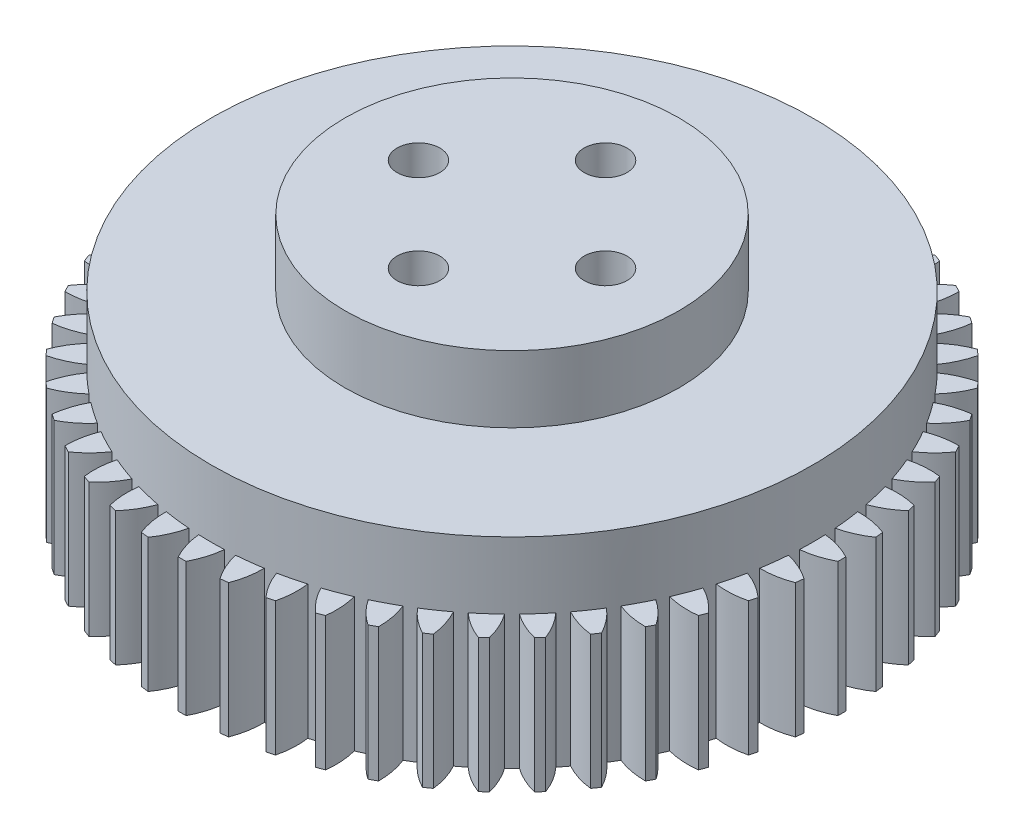
SolidWorks part; units mm, degrees
ref_plane "Front" through (0, 0, 0) normal (0, 0, 1) x (1, 0, 0)
ref_plane "Top" through (0, 0, 0) normal (0, 1, 0) x (1, 0, 0)
ref_plane "Right" through (0, 0, 0) normal (1, 0, 0) x (0, 0, -1)
sketch "Sketch1" plane through (0, 0, 0) normal (0, 1, 0) x (1, 0, 0)
  circle A0 centre (0, 0) radius 22.5
  dimension "D1" = 45
extrude "Boss-Extrude1" add sketch "Sketch1" along normal blind 15
sketch "Sketch2" plane through (0, 15, 0) normal (0, 1, 0) x (1, 0, 0)
  circle A0 centre (0, 0) radius 12.5
  dimension "D1" = 25
extrude "Boss-Extrude2" add sketch "Sketch2" along normal blind 5
sketch "Sketch3" plane through (0, 20, 0) normal (0, 1, 0) x (1, 0, 0)
  circle A1 centre (7, 0) radius 1.6
  circle A2 centre (0, -7) radius 1.6
  circle A3 centre (-7, 0) radius 1.6
  circle A4 centre (0, 7) radius 1.6
  point P13 (0, 0)
  dimension "D2" = 3.2
  dimension "D4" = 4
extrude "Cut-Extrude2" cut sketch "Sketch3" against normal blind 21
sketch "Sketch4" plane through (0, 0, 0) normal (0, -1, 0) x (1, 0, 0)
  circle A0 centre (0, -7) radius 3
  circle A1 centre (-7, 0) radius 3
  circle A2 centre (0, 7) radius 3
  circle A3 centre (7, 0) radius 3
  point P11 (0, 0)
  dimension "D1" = 6
  dimension "D2" = 4
extrude "Cut-Extrude3" cut sketch "Sketch4" against normal blind 4
sketch "Sketch5" plane through (0, 0, 0) normal (0, -1, 0) x (1, 0, 0)
  arc A0 (-0.2927, 24.6828) -> (-0.9725, 22.4) centre (5.0034, 21.8629) ccw
  arc A1 (0.9725, 22.4) -> (0.2927, 24.6828) centre (-5.0034, 21.8629) ccw
  arc A2 (0.2927, 24.6828) -> (-0.2927, 24.6828) centre (0, 0) ccw
  arc A3 (-0.9725, 22.4) -> (0.9725, 22.4) centre (0, 0) cw
  arc A4 (2.6847, 24.5381) -> (1.7346, 22.3539) centre (7.6022, 21.1004) ccw
  arc A5 (3.6654, 22.1195) -> (3.2657, 24.4675) centre (-2.3317, 22.3066) ccw
  arc A6 (3.2657, 24.4675) -> (2.6847, 24.5381) centre (0, 0) ccw
  arc A7 (1.7346, 22.3539) -> (3.6654, 22.1195) centre (0, 0) cw
  arc A8 (5.6228, 24.0356) -> (4.4164, 21.9818) centre (10.0902, 20.0302) ccw
  arc A9 (6.3049, 21.5164) -> (6.1911, 23.8955) centre (0.3741, 22.425) ccw
  arc A10 (6.1911, 23.8955) -> (5.6228, 24.0356) centre (0, 0) ccw
  arc A11 (4.4164, 21.9818) -> (6.3049, 21.5164) centre (0, 0) cw
  arc A12 (8.479, 23.1826) -> (7.0339, 21.2892) centre (12.431, 18.6679) ccw
  arc A13 (8.8524, 20.5995) -> (9.0263, 22.975) centre (3.0744, 22.2164) ccw
  arc A14 (9.0263, 22.975) -> (8.479, 23.1826) centre (0, 0) ccw
  arc A15 (7.0339, 21.2892) -> (8.8524, 20.5995) centre (0, 0) cw
  arc A16 (11.2115, 21.9915) -> (9.5487, 20.2862) centre (14.5905, 17.0334) ccw
  arc A17 (11.2709, 19.3823) -> (11.7298, 21.7195) centre (5.7299, 21.6838) ccw
  arc A18 (11.7298, 21.7195) -> (11.2115, 21.9915) centre (0, 0) ccw
  arc A19 (9.5487, 20.2862) -> (11.2709, 19.3823) centre (0, 0) cw
  arc A20 (13.7806, 20.4798) -> (11.9243, 18.9873) centre (16.5373, 15.1506) ccw
  arc A21 (13.525, 17.8824) -> (14.2623, 20.1473) centre (8.3018, 20.8351) ccw
  arc A22 (14.2623, 20.1473) -> (13.7806, 20.4798) centre (0, 0) ccw
  arc A23 (11.9243, 18.9873) -> (13.525, 17.8824) centre (0, 0) cw
  arc A24 (16.1486, 18.6694) -> (14.126, 17.4115) centre (18.2429, 13.0467) ccw
  arc A25 (15.5819, 16.1218) -> (16.5868, 18.2812) centre (10.7527, 19.6825) ccw
  arc A26 (16.5868, 18.2812) -> (16.1486, 18.6694) centre (0, 0) ccw
  arc A27 (14.126, 17.4115) -> (15.5819, 16.1218) centre (0, 0) cw
  arc A28 (18.2812, 16.5868) -> (16.1218, 15.5819) centre (19.6825, 10.7527) ccw
  arc A29 (17.4115, 14.126) -> (18.6694, 16.1486) centre (13.0467, 18.2429) ccw
  arc A30 (18.6694, 16.1486) -> (18.2812, 16.5868) centre (0, 0) ccw
  arc A31 (16.1218, 15.5819) -> (17.4115, 14.126) centre (0, 0) cw
  arc A32 (20.1473, 14.2623) -> (17.8824, 13.525) centre (20.8351, 8.3018) ccw
  arc A33 (18.9873, 11.9243) -> (20.4798, 13.7806) centre (15.1506, 16.5373) ccw
  arc A34 (20.4798, 13.7806) -> (20.1473, 14.2623) centre (0, 0) ccw
  arc A35 (17.8824, 13.525) -> (18.9873, 11.9243) centre (0, 0) cw
  arc A36 (21.7195, 11.7298) -> (19.3823, 11.2709) centre (21.6838, 5.7299) ccw
  arc A37 (20.2862, 9.5487) -> (21.9915, 11.2115) centre (17.0334, 14.5905) ccw
  arc A38 (21.9915, 11.2115) -> (21.7195, 11.7298) centre (0, 0) ccw
  arc A39 (19.3823, 11.2709) -> (20.2862, 9.5487) centre (0, 0) cw
  arc A40 (22.975, 9.0263) -> (20.5995, 8.8524) centre (22.2164, 3.0744) ccw
  arc A41 (21.2892, 7.0339) -> (23.1826, 8.479) centre (18.6679, 12.431) ccw
  arc A42 (23.1826, 8.479) -> (22.975, 9.0263) centre (0, 0) ccw
  arc A43 (20.5995, 8.8524) -> (21.2892, 7.0339) centre (0, 0) cw
  arc A44 (23.8955, 6.1911) -> (21.5164, 6.3049) centre (22.425, 0.3741) ccw
  arc A45 (21.9818, 4.4164) -> (24.0356, 5.6228) centre (20.0302, 10.0902) ccw
  arc A46 (24.0356, 5.6228) -> (23.8955, 6.1911) centre (0, 0) ccw
  arc A47 (21.5164, 6.3049) -> (21.9818, 4.4164) centre (0, 0) cw
  arc A48 (24.4675, 3.2657) -> (22.1195, 3.6654) centre (22.3066, -2.3317) ccw
  arc A49 (22.3539, 1.7346) -> (24.5381, 2.6847) centre (21.1004, 7.6022) ccw
  arc A50 (24.5381, 2.6847) -> (24.4675, 3.2657) centre (0, 0) ccw
  arc A51 (22.1195, 3.6654) -> (22.3539, 1.7346) centre (0, 0) cw
  arc A52 (24.6828, 0.2927) -> (22.4, 0.9725) centre (21.8629, -5.0034) ccw
  arc A53 (22.4, -0.9725) -> (24.6828, -0.2927) centre (21.8629, 5.0034) ccw
  arc A54 (24.6828, -0.2927) -> (24.6828, 0.2927) centre (0, 0) ccw
  arc A55 (22.4, 0.9725) -> (22.4, -0.9725) centre (0, 0) cw
  arc A56 (24.5381, -2.6847) -> (22.3539, -1.7346) centre (21.1004, -7.6022) ccw
  arc A57 (22.1195, -3.6654) -> (24.4675, -3.2657) centre (22.3066, 2.3317) ccw
  arc A58 (24.4675, -3.2657) -> (24.5381, -2.6847) centre (0, 0) ccw
  arc A59 (22.3539, -1.7346) -> (22.1195, -3.6654) centre (0, 0) cw
  arc A60 (24.0356, -5.6228) -> (21.9818, -4.4164) centre (20.0302, -10.0902) ccw
  arc A61 (21.5164, -6.3049) -> (23.8955, -6.1911) centre (22.425, -0.3741) ccw
  arc A62 (23.8955, -6.1911) -> (24.0356, -5.6228) centre (0, 0) ccw
  arc A63 (21.9818, -4.4164) -> (21.5164, -6.3049) centre (0, 0) cw
  arc A64 (23.1826, -8.479) -> (21.2892, -7.0339) centre (18.6679, -12.431) ccw
  arc A65 (20.5995, -8.8524) -> (22.975, -9.0263) centre (22.2164, -3.0744) ccw
  arc A66 (22.975, -9.0263) -> (23.1826, -8.479) centre (0, 0) ccw
  arc A67 (21.2892, -7.0339) -> (20.5995, -8.8524) centre (0, 0) cw
  arc A68 (21.9915, -11.2115) -> (20.2862, -9.5487) centre (17.0334, -14.5905) ccw
  arc A69 (19.3823, -11.2709) -> (21.7195, -11.7298) centre (21.6838, -5.7299) ccw
  arc A70 (21.7195, -11.7298) -> (21.9915, -11.2115) centre (0, 0) ccw
  arc A71 (20.2862, -9.5487) -> (19.3823, -11.2709) centre (0, 0) cw
  arc A72 (20.4798, -13.7806) -> (18.9873, -11.9243) centre (15.1506, -16.5373) ccw
  arc A73 (17.8824, -13.525) -> (20.1473, -14.2623) centre (20.8351, -8.3018) ccw
  arc A74 (20.1473, -14.2623) -> (20.4798, -13.7806) centre (0, 0) ccw
  arc A75 (18.9873, -11.9243) -> (17.8824, -13.525) centre (0, 0) cw
  arc A76 (18.6694, -16.1486) -> (17.4115, -14.126) centre (13.0467, -18.2429) ccw
  arc A77 (16.1218, -15.5819) -> (18.2812, -16.5868) centre (19.6825, -10.7527) ccw
  arc A78 (18.2812, -16.5868) -> (18.6694, -16.1486) centre (0, 0) ccw
  arc A79 (17.4115, -14.126) -> (16.1218, -15.5819) centre (0, 0) cw
  arc A80 (16.5868, -18.2812) -> (15.5819, -16.1218) centre (10.7527, -19.6825) ccw
  arc A81 (14.126, -17.4115) -> (16.1486, -18.6694) centre (18.2429, -13.0467) ccw
  arc A82 (16.1486, -18.6694) -> (16.5868, -18.2812) centre (0, 0) ccw
  arc A83 (15.5819, -16.1218) -> (14.126, -17.4115) centre (0, 0) cw
  arc A84 (14.2623, -20.1473) -> (13.525, -17.8824) centre (8.3018, -20.8351) ccw
  arc A85 (11.9243, -18.9873) -> (13.7806, -20.4798) centre (16.5373, -15.1506) ccw
  arc A86 (13.7806, -20.4798) -> (14.2623, -20.1473) centre (0, 0) ccw
  arc A87 (13.525, -17.8824) -> (11.9243, -18.9873) centre (0, 0) cw
  arc A88 (11.7298, -21.7195) -> (11.2709, -19.3823) centre (5.7299, -21.6838) ccw
  arc A89 (9.5487, -20.2862) -> (11.2115, -21.9915) centre (14.5905, -17.0334) ccw
  arc A90 (11.2115, -21.9915) -> (11.7298, -21.7195) centre (0, 0) ccw
  arc A91 (11.2709, -19.3823) -> (9.5487, -20.2862) centre (0, 0) cw
  arc A92 (9.0263, -22.975) -> (8.8524, -20.5995) centre (3.0744, -22.2164) ccw
  arc A93 (7.0339, -21.2892) -> (8.479, -23.1826) centre (12.431, -18.6679) ccw
  arc A94 (8.479, -23.1826) -> (9.0263, -22.975) centre (0, 0) ccw
  arc A95 (8.8524, -20.5995) -> (7.0339, -21.2892) centre (0, 0) cw
  arc A96 (6.1911, -23.8955) -> (6.3049, -21.5164) centre (0.3741, -22.425) ccw
  arc A97 (4.4164, -21.9818) -> (5.6228, -24.0356) centre (10.0902, -20.0302) ccw
  arc A98 (5.6228, -24.0356) -> (6.1911, -23.8955) centre (0, 0) ccw
  arc A99 (6.3049, -21.5164) -> (4.4164, -21.9818) centre (0, 0) cw
  arc A100 (3.2657, -24.4675) -> (3.6654, -22.1195) centre (-2.3317, -22.3066) ccw
  arc A101 (1.7346, -22.3539) -> (2.6847, -24.5381) centre (7.6022, -21.1004) ccw
  arc A102 (2.6847, -24.5381) -> (3.2657, -24.4675) centre (0, 0) ccw
  arc A103 (3.6654, -22.1195) -> (1.7346, -22.3539) centre (0, 0) cw
  arc A104 (0.2927, -24.6828) -> (0.9725, -22.4) centre (-5.0034, -21.8629) ccw
  arc A105 (-0.9725, -22.4) -> (-0.2927, -24.6828) centre (5.0034, -21.8629) ccw
  arc A106 (-0.2927, -24.6828) -> (0.2927, -24.6828) centre (0, 0) ccw
  arc A107 (0.9725, -22.4) -> (-0.9725, -22.4) centre (0, 0) cw
  arc A108 (-2.6847, -24.5381) -> (-1.7346, -22.3539) centre (-7.6022, -21.1004) ccw
  arc A109 (-3.6654, -22.1195) -> (-3.2657, -24.4675) centre (2.3317, -22.3066) ccw
  arc A110 (-3.2657, -24.4675) -> (-2.6847, -24.5381) centre (0, 0) ccw
  arc A111 (-1.7346, -22.3539) -> (-3.6654, -22.1195) centre (0, 0) cw
  arc A112 (-5.6228, -24.0356) -> (-4.4164, -21.9818) centre (-10.0902, -20.0302) ccw
  arc A113 (-6.3049, -21.5164) -> (-6.1911, -23.8955) centre (-0.3741, -22.425) ccw
  arc A114 (-6.1911, -23.8955) -> (-5.6228, -24.0356) centre (0, 0) ccw
  arc A115 (-4.4164, -21.9818) -> (-6.3049, -21.5164) centre (0, 0) cw
  arc A116 (-8.479, -23.1826) -> (-7.0339, -21.2892) centre (-12.431, -18.6679) ccw
  arc A117 (-8.8524, -20.5995) -> (-9.0263, -22.975) centre (-3.0744, -22.2164) ccw
  arc A118 (-9.0263, -22.975) -> (-8.479, -23.1826) centre (0, 0) ccw
  arc A119 (-7.0339, -21.2892) -> (-8.8524, -20.5995) centre (0, 0) cw
  arc A120 (-11.2115, -21.9915) -> (-9.5487, -20.2862) centre (-14.5905, -17.0334) ccw
  arc A121 (-11.2709, -19.3823) -> (-11.7298, -21.7195) centre (-5.7299, -21.6838) ccw
  arc A122 (-11.7298, -21.7195) -> (-11.2115, -21.9915) centre (0, 0) ccw
  arc A123 (-9.5487, -20.2862) -> (-11.2709, -19.3823) centre (0, 0) cw
  arc A124 (-13.7806, -20.4798) -> (-11.9243, -18.9873) centre (-16.5373, -15.1506) ccw
  arc A125 (-13.525, -17.8824) -> (-14.2623, -20.1473) centre (-8.3018, -20.8351) ccw
  arc A126 (-14.2623, -20.1473) -> (-13.7806, -20.4798) centre (0, 0) ccw
  arc A127 (-11.9243, -18.9873) -> (-13.525, -17.8824) centre (0, 0) cw
  arc A128 (-16.1486, -18.6694) -> (-14.126, -17.4115) centre (-18.2429, -13.0467) ccw
  arc A129 (-15.5819, -16.1218) -> (-16.5868, -18.2812) centre (-10.7527, -19.6825) ccw
  arc A130 (-16.5868, -18.2812) -> (-16.1486, -18.6694) centre (0, 0) ccw
  arc A131 (-14.126, -17.4115) -> (-15.5819, -16.1218) centre (0, 0) cw
  arc A132 (-18.2812, -16.5868) -> (-16.1218, -15.5819) centre (-19.6825, -10.7527) ccw
  arc A133 (-17.4115, -14.126) -> (-18.6694, -16.1486) centre (-13.0467, -18.2429) ccw
  arc A134 (-18.6694, -16.1486) -> (-18.2812, -16.5868) centre (0, 0) ccw
  arc A135 (-16.1218, -15.5819) -> (-17.4115, -14.126) centre (0, 0) cw
  arc A136 (-20.1473, -14.2623) -> (-17.8824, -13.525) centre (-20.8351, -8.3018) ccw
  arc A137 (-18.9873, -11.9243) -> (-20.4798, -13.7806) centre (-15.1506, -16.5373) ccw
  arc A138 (-20.4798, -13.7806) -> (-20.1473, -14.2623) centre (0, 0) ccw
  arc A139 (-17.8824, -13.525) -> (-18.9873, -11.9243) centre (0, 0) cw
  arc A140 (-21.7195, -11.7298) -> (-19.3823, -11.2709) centre (-21.6838, -5.7299) ccw
  arc A141 (-20.2862, -9.5487) -> (-21.9915, -11.2115) centre (-17.0334, -14.5905) ccw
  arc A142 (-21.9915, -11.2115) -> (-21.7195, -11.7298) centre (0, 0) ccw
  arc A143 (-19.3823, -11.2709) -> (-20.2862, -9.5487) centre (0, 0) cw
  arc A144 (-22.975, -9.0263) -> (-20.5995, -8.8524) centre (-22.2164, -3.0744) ccw
  arc A145 (-21.2892, -7.0339) -> (-23.1826, -8.479) centre (-18.6679, -12.431) ccw
  arc A146 (-23.1826, -8.479) -> (-22.975, -9.0263) centre (0, 0) ccw
  arc A147 (-20.5995, -8.8524) -> (-21.2892, -7.0339) centre (0, 0) cw
  arc A148 (-23.8955, -6.1911) -> (-21.5164, -6.3049) centre (-22.425, -0.3741) ccw
  arc A149 (-21.9818, -4.4164) -> (-24.0356, -5.6228) centre (-20.0302, -10.0902) ccw
  arc A150 (-24.0356, -5.6228) -> (-23.8955, -6.1911) centre (0, 0) ccw
  arc A151 (-21.5164, -6.3049) -> (-21.9818, -4.4164) centre (0, 0) cw
  arc A152 (-24.4675, -3.2657) -> (-22.1195, -3.6654) centre (-22.3066, 2.3317) ccw
  arc A153 (-22.3539, -1.7346) -> (-24.5381, -2.6847) centre (-21.1004, -7.6022) ccw
  arc A154 (-24.5381, -2.6847) -> (-24.4675, -3.2657) centre (0, 0) ccw
  arc A155 (-22.1195, -3.6654) -> (-22.3539, -1.7346) centre (0, 0) cw
  arc A156 (-24.6828, -0.2927) -> (-22.4, -0.9725) centre (-21.8629, 5.0034) ccw
  arc A157 (-22.4, 0.9725) -> (-24.6828, 0.2927) centre (-21.8629, -5.0034) ccw
  arc A158 (-24.6828, 0.2927) -> (-24.6828, -0.2927) centre (0, 0) ccw
  arc A159 (-22.4, -0.9725) -> (-22.4, 0.9725) centre (0, 0) cw
  arc A160 (-24.5381, 2.6847) -> (-22.3539, 1.7346) centre (-21.1004, 7.6022) ccw
  arc A161 (-22.1195, 3.6654) -> (-24.4675, 3.2657) centre (-22.3066, -2.3317) ccw
  arc A162 (-24.4675, 3.2657) -> (-24.5381, 2.6847) centre (0, 0) ccw
  arc A163 (-22.3539, 1.7346) -> (-22.1195, 3.6654) centre (0, 0) cw
  arc A164 (-24.0356, 5.6228) -> (-21.9818, 4.4164) centre (-20.0302, 10.0902) ccw
  arc A165 (-21.5164, 6.3049) -> (-23.8955, 6.1911) centre (-22.425, 0.3741) ccw
  arc A166 (-23.8955, 6.1911) -> (-24.0356, 5.6228) centre (0, 0) ccw
  arc A167 (-21.9818, 4.4164) -> (-21.5164, 6.3049) centre (0, 0) cw
  arc A168 (-23.1826, 8.479) -> (-21.2892, 7.0339) centre (-18.6679, 12.431) ccw
  arc A169 (-20.5995, 8.8524) -> (-22.975, 9.0263) centre (-22.2164, 3.0744) ccw
  arc A170 (-22.975, 9.0263) -> (-23.1826, 8.479) centre (0, 0) ccw
  arc A171 (-21.2892, 7.0339) -> (-20.5995, 8.8524) centre (0, 0) cw
  arc A172 (-21.9915, 11.2115) -> (-20.2862, 9.5487) centre (-17.0334, 14.5905) ccw
  arc A173 (-19.3823, 11.2709) -> (-21.7195, 11.7298) centre (-21.6838, 5.7299) ccw
  arc A174 (-21.7195, 11.7298) -> (-21.9915, 11.2115) centre (0, 0) ccw
  arc A175 (-20.2862, 9.5487) -> (-19.3823, 11.2709) centre (0, 0) cw
  arc A176 (-20.4798, 13.7806) -> (-18.9873, 11.9243) centre (-15.1506, 16.5373) ccw
  arc A177 (-17.8824, 13.525) -> (-20.1473, 14.2623) centre (-20.8351, 8.3018) ccw
  arc A178 (-20.1473, 14.2623) -> (-20.4798, 13.7806) centre (0, 0) ccw
  arc A179 (-18.9873, 11.9243) -> (-17.8824, 13.525) centre (0, 0) cw
  arc A180 (-18.6694, 16.1486) -> (-17.4115, 14.126) centre (-13.0467, 18.2429) ccw
  arc A181 (-16.1218, 15.5819) -> (-18.2812, 16.5868) centre (-19.6825, 10.7527) ccw
  arc A182 (-18.2812, 16.5868) -> (-18.6694, 16.1486) centre (0, 0) ccw
  arc A183 (-17.4115, 14.126) -> (-16.1218, 15.5819) centre (0, 0) cw
  arc A184 (-16.5868, 18.2812) -> (-15.5819, 16.1218) centre (-10.7527, 19.6825) ccw
  arc A185 (-14.126, 17.4115) -> (-16.1486, 18.6694) centre (-18.2429, 13.0467) ccw
  arc A186 (-16.1486, 18.6694) -> (-16.5868, 18.2812) centre (0, 0) ccw
  arc A187 (-15.5819, 16.1218) -> (-14.126, 17.4115) centre (0, 0) cw
  arc A188 (-14.2623, 20.1473) -> (-13.525, 17.8824) centre (-8.3018, 20.8351) ccw
  arc A189 (-11.9243, 18.9873) -> (-13.7806, 20.4798) centre (-16.5373, 15.1506) ccw
  arc A190 (-13.7806, 20.4798) -> (-14.2623, 20.1473) centre (0, 0) ccw
  arc A191 (-13.525, 17.8824) -> (-11.9243, 18.9873) centre (0, 0) cw
  arc A192 (-11.7298, 21.7195) -> (-11.2709, 19.3823) centre (-5.7299, 21.6838) ccw
  arc A193 (-9.5487, 20.2862) -> (-11.2115, 21.9915) centre (-14.5905, 17.0334) ccw
  arc A194 (-11.2115, 21.9915) -> (-11.7298, 21.7195) centre (0, 0) ccw
  arc A195 (-11.2709, 19.3823) -> (-9.5487, 20.2862) centre (0, 0) cw
  arc A196 (-9.0263, 22.975) -> (-8.8524, 20.5995) centre (-3.0744, 22.2164) ccw
  arc A197 (-7.0339, 21.2892) -> (-8.479, 23.1826) centre (-12.431, 18.6679) ccw
  arc A198 (-8.479, 23.1826) -> (-9.0263, 22.975) centre (0, 0) ccw
  arc A199 (-8.8524, 20.5995) -> (-7.0339, 21.2892) centre (0, 0) cw
  arc A200 (-6.1911, 23.8955) -> (-6.3049, 21.5164) centre (-0.3741, 22.425) ccw
  arc A201 (-4.4164, 21.9818) -> (-5.6228, 24.0356) centre (-10.0902, 20.0302) ccw
  arc A202 (-5.6228, 24.0356) -> (-6.1911, 23.8955) centre (0, 0) ccw
  arc A203 (-6.3049, 21.5164) -> (-4.4164, 21.9818) centre (0, 0) cw
  arc A204 (-3.2657, 24.4675) -> (-3.6654, 22.1195) centre (2.3317, 22.3066) ccw
  arc A205 (-1.7346, 22.3539) -> (-2.6847, 24.5381) centre (-7.6022, 21.1004) ccw
  arc A206 (-2.6847, 24.5381) -> (-3.2657, 24.4675) centre (0, 0) ccw
  arc A207 (-3.6654, 22.1195) -> (-1.7346, 22.3539) centre (0, 0) cw
  point P315 (0, 0)
  dimension "D1" = 0.9725
  dimension "D2" = 0.9725
  dimension "D3" = 0.2927
  dimension "D4" = 0.2927
  dimension "D5" = 2.2828
  dimension "D6" = 22.4
  dimension "D7" = 52
extrude "Boss-Extrude3" add sketch "Sketch5" against normal blind 10
sketch "Sketch7" plane through (0, 0, 0) normal (0, -1, 0) x (1, 0, 0)
  circle A0 centre (0, 0) radius 4
  dimension "D1" = 8
extrude "Boss-Extrude5" add sketch "Sketch7" along normal blind 9
sketch "Sketch8" plane through (0, -9, 0) normal (0, -1, 0) x (1, 0, 0)
  circle A0 centre (0, 0) radius 0.8
  circle A1 centre (0, 0) radius 4 construction
  dimension "D1" = 3.2
extrude "Cut-Extrude4" cut sketch "Sketch8" against normal blind 24
